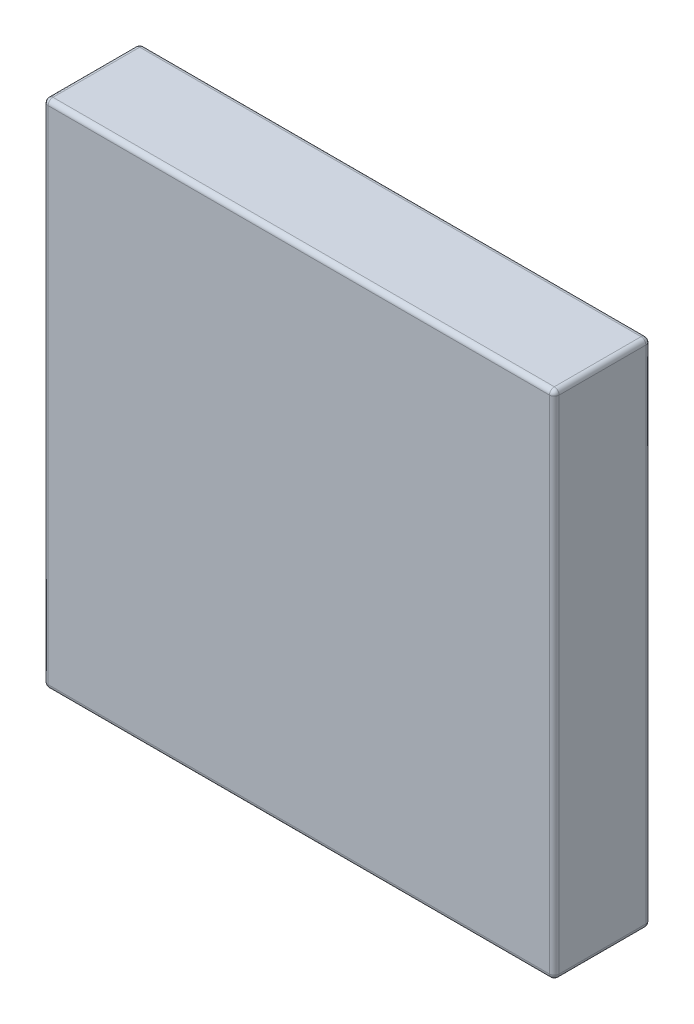
SolidWorks part; units mm, degrees
ref_plane "前视基准面" through (0, 0, 0) normal (0, 0, 1) x (1, 0, 0)
ref_plane "上视基准面" through (0, 0, 0) normal (0, 1, 0) x (1, 0, 0)
ref_plane "右视基准面" through (0, 0, 0) normal (1, 0, 0) x (0, 0, -1)
sketch "草图1" plane through (0, 0, 0) normal (0, 0, 1) x (1, 0, 0)
  line L20 (53.033, 53.033) -> (53.033, 0)
  line L21 (0, 0) -> (0, 53.033)
  line L22 (53.033, 53.033) -> (0, 53.033)
  line L23 (53.033, 0) -> (0, 0)
  dimension "D6" = 75
  dimension "D7" = 75
extrude "凸台-拉伸1" add sketch "草图1" along normal blind 10
fillet "圆角1" radius 0.5 12 edges at (53.033, 26.5165, 0) (26.5165, 53.033, 0) (26.5165, 0, 10) (53.033, 26.5165, 10) (26.5165, 53.033, 10) (0, 26.5165, 10) (0, 53.033, 5) (53.033, 53.033, 5) (53.033, 0, 5) (0, 0, 5) (0, 26.5165, 0) (26.5165, 0, 0)
